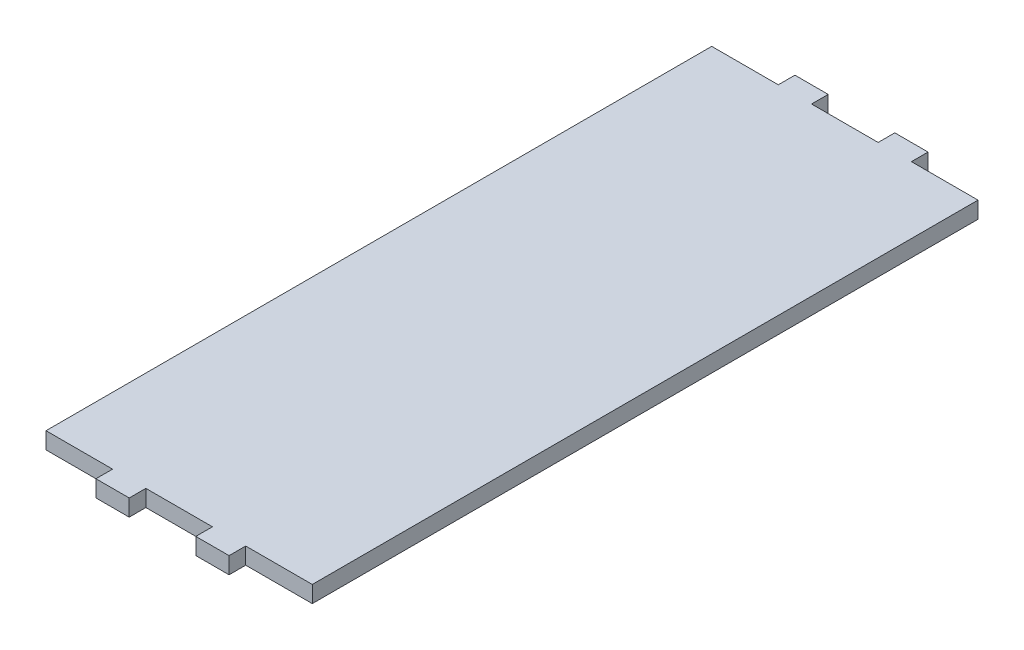
SolidWorks part; units mm, degrees
material "Acrylic (Medium-high impact)"
ref_plane "Front Plane" through (0, 0, 0) normal (0, 0, 1) x (1, 0, 0)
ref_plane "Top Plane" through (0, 0, 0) normal (0, 1, 0) x (1, 0, 0)
ref_plane "Right Plane" through (0, 0, 0) normal (1, 0, 0) x (0, 0, -1)
sketch "Sketch1" plane through (0, 0, 0) normal (0, 1, 0) x (1, 0, 0)
  line L0 (-6.35, 65.0875) -> (6.35, 65.0875) construction
  line L1 (-25.4, 63.5) -> (25.4, 63.5)
  line L2 (-25.4, 63.5) -> (-25.4, -63.5)
  line L3 (-25.4, -63.5) -> (25.4, -63.5)
  line L4 (25.4, 63.5) -> (25.4, -63.5)
  line L5 (-25.4, 63.5) -> (25.4, -63.5) construction
  line L6 (-25.4, -63.5) -> (25.4, 63.5) construction
  line L7 (-12.7, 63.5) -> (-6.35, 63.5)
  line L8 (-12.7, 63.5) -> (-12.7, 66.675)
  line L9 (-12.7, 66.675) -> (-6.35, 66.675)
  line L10 (-6.35, 63.5) -> (-6.35, 66.675)
  line L11 (6.35, 63.5) -> (12.7, 63.5)
  line L12 (6.35, 63.5) -> (6.35, 66.675)
  line L13 (6.35, 66.675) -> (12.7, 66.675)
  line L14 (12.7, 63.5) -> (12.7, 66.675)
  line L15 (-12.7, -63.5) -> (-6.35, -63.5)
  line L16 (-12.7, -63.5) -> (-12.7, -66.675)
  line L17 (-12.7, -66.675) -> (-6.35, -66.675)
  line L18 (-6.35, -63.5) -> (-6.35, -66.675)
  line L19 (6.35, -63.5) -> (12.7, -63.5)
  line L20 (6.35, -63.5) -> (6.35, -66.675)
  line L21 (6.35, -66.675) -> (12.7, -66.675)
  line L22 (12.7, -63.5) -> (12.7, -66.675)
  point P0 (0, 0)
  point P24 (0, 65.0875)
  point P25 (15.7815, 69.6167)
  dimension "D1" = 127
  dimension "D2" = 50.8
  dimension "D3" = 6.35
  dimension "D4" = 3.175
  dimension "D5" = 6.35
extrude "Boss-Extrude1" add sketch "Sketch1" along normal blind 3.175 contours L4 L1 L2 L3 | L22 L3 L20 L21 | L18 L3 L16 L17 | L1 L10 L9 L8 | L1 L14 L13 L12
equation "\"WallThickness\"=0.125"
equation "\"D1@Boss-Extrude1\"=\"WallThickness\""
